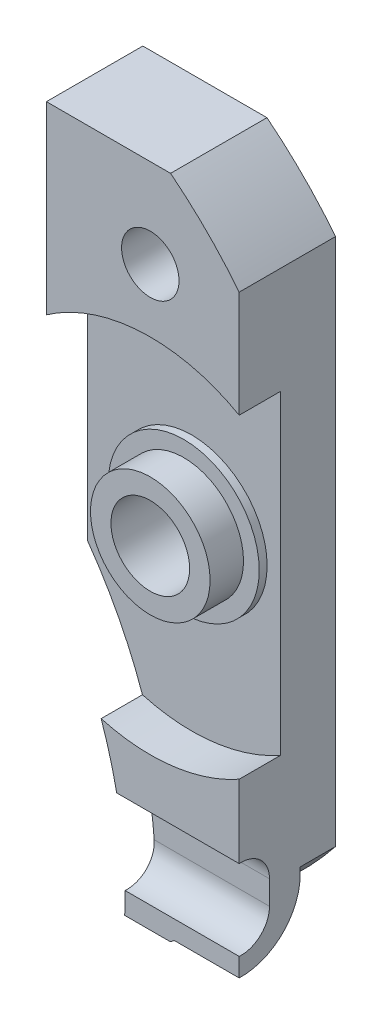
SolidWorks part; units mm, degrees
material "ABS"
ref_plane "Front Plane" through (0, 0, 0) normal (0, 0, 1) x (1, 0, 0)
ref_plane "Top Plane" through (0, 0, 0) normal (0, 1, 0) x (1, 0, 0)
ref_plane "Right Plane" through (0, 0, 0) normal (1, 0, 0) x (0, 0, -1)
sketch "Sketch1" plane through (0, 0, 0) normal (0, 0, 1) x (1, 0, 0)
  line L1 (-6.125, -21.15) -> (6.125, -21.15)
  line L2 (-6.125, -21.15) -> (-6.125, 21.15)
  line L3 (-6.125, 21.15) -> (6.125, 21.15)
  line L4 (6.125, -21.15) -> (6.125, 21.15)
  line L5 (-6.125, -21.15) -> (6.125, 21.15) construction
  line L6 (-6.125, 21.15) -> (6.125, -21.15) construction
  point P0 (0, 0)
  dimension "D1" = 12.25
  dimension "D2" = 42.3
extrude "Boss-Extrude1" add sketch "Sketch1" along normal blind 6.125
sketch "Sketch2" plane through (0, 0, 6.125) normal (0, 0, 1) x (1, 0, 0)
  line L0 (6.125, 21.15) -> (-6.125, 21.15) construction
  line L1 (-6.125, 21.15) -> (-6.125, -21.15) construction
  circle A0 centre (0.475, 15.5) radius 1.825
  circle A1 centre (0.475, 0) radius 2.5
  dimension "D1" = 3.65
  dimension "D2" = 5
  dimension "D3" = 5.65
  dimension "D4" = 6.6
  dimension "D5" = 15.5
extrude "Cut-Extrude1" cut sketch "Sketch2" against normal through all
sketch "Sketch3" plane through (0, 0, 6.125) normal (0, 0, 1) x (1, 0, 0)
  line L0 (6.125, 21.15) -> (-6.125, 21.15) construction
  line L1 (-6.125, 21.15) -> (-6.125, -21.15) construction
  line L2 (-6.125, -21.15) -> (6.125, -21.15) construction
  line L4 (-6.125, -21.15) -> (-1.1519, -21.15)
  line L5 (-6.125, -4.3518) -> (-6.125, -21.15)
  line L6 (6.125, -21.15) -> (6.125, 21.15) construction
  line L7 (6.125, 21.15) -> (1.7648, 21.15)
  line L8 (6.125, 16.7898) -> (6.125, 21.15)
  line L9 (6.125, -21.15) -> (1.7575, -21.15)
  line L10 (-6.125, -21.15) -> (6.125, -21.15) construction
  line L11 (6.125, -21.15) -> (6.125, -16.784)
  arc A0 (6.125, 16.7898) -> (1.7648, 21.15) centre (-15.0221, 0.0029) ccw
  arc A1 (-1.1519, -21.15) -> (-6.125, -4.3518) centre (-28.1274, -20.0009) ccw
  arc A2 (1.7575, -21.15) -> (6.125, -16.784) centre (-15.0221, 0.0029) ccw
  dimension "D1" = 27
  dimension "D2" = 27
  dimension "D3" = 8.8971
  dimension "D4" = 21.1471
  dimension "D5" = 41.1509
  dimension "D6" = 22.0024
extrude "Cut-Extrude2" cut sketch "Sketch3" against normal through all
sketch "Sketch4" plane through (0, 0, 6.125) normal (0, 0, 1) x (1, 0, 0)
  circle A0 centre (0.475, 0) radius 11.5
  dimension "D1" = 23
extrude "Cut-Extrude3" cut sketch "Sketch4" against normal blind 2.625
sketch "Sketch5" plane through (0, 0, 3.5) normal (0, 0, 1) x (1, 0, 0)
  circle A0 centre (0.475, 0) radius 4.8
  circle A1 centre (0.475, 0) radius 2.5 construction
  circle A2 centre (0.475, 0) radius 2.5
  dimension "D1" = 9.6
extrude "Boss-Extrude2" add sketch "Sketch5" along normal blind 0.5
sketch "Sketch6" plane through (0, 0, 4) normal (0, 0, 1) x (1, 0, 0)
  circle A0 centre (0.475, 0) radius 3.8
  circle A1 centre (0.475, 0) radius 2.5 construction
  circle A2 centre (0.475, 0) radius 2.5
  dimension "D1" = 7.6
extrude "Boss-Extrude3" add sketch "Sketch6" along normal blind 2.125
sketch "Sketch7" plane through (6.125, 0, 0) normal (1, 0, 0) x (0, 0, -1)
  line L0 (0, -16.784) -> (0, 16.7898) construction
  line L1 (-3.5, -10.0164) -> (-6.125, -10.0164) construction
  line L2 (-6.125, -13.4621) -> (-6.125, -20.9579)
  line L5 (-6.125, -16.784) -> (-6.125, -10.0164) construction
  arc A0 (-6.125, -20.9579) -> (-6.125, -13.4621) centre (-6, -17.21) ccw
  dimension "D1" = 7.5
  dimension "D2" = 6
  dimension "D3" = 7.1936
extrude "Boss-Extrude4" add sketch "Sketch7" against normal up to next
sketch "Sketch8" plane through (6.125, 0, 0) normal (1, 0, 0) x (0, 0, -1)
  line L0 (-6, -17.9736) -> (-6, -16.4595) construction
  line L1 (-7.8, -17.9736) -> (-7.8, -16.4595)
  line L2 (-4.2, -17.9736) -> (-4.2, -16.4595)
  line L3 (0, -16.784) -> (0, 16.7898) construction
  line L4 (-3.5, -10.0164) -> (-6.125, -10.0164) construction
  arc A0 (-7.8, -17.9736) -> (-4.2, -17.9736) centre (-6, -17.9736) ccw
  arc A1 (-4.2, -16.4595) -> (-7.8, -16.4595) centre (-6, -16.4595) ccw
  point P2 (-6, -17.2165)
  dimension "D4" = 6.4431
  dimension "D1" = 3.6
  dimension "D2" = 6
  dimension "D3" = 1.5141
extrude "Cut-Extrude4" cut sketch "Sketch8" against normal through all
